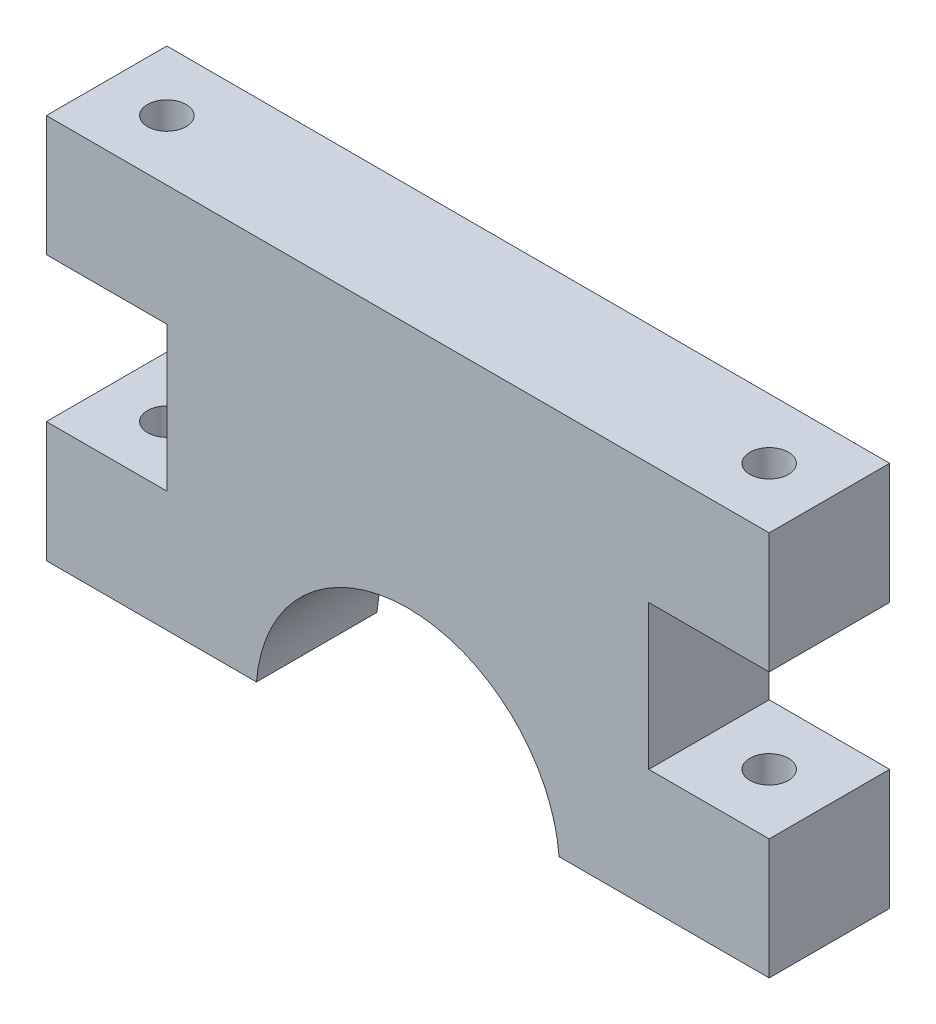
SolidWorks part; units mm, degrees
ref_plane "Спереди" through (0, 0, 0) normal (0, 0, 1) x (1, 0, 0)
ref_plane "Сверху" through (0, 0, 0) normal (0, 1, 0) x (1, 0, 0)
ref_plane "Справа" through (0, 0, 0) normal (1, 0, 0) x (0, 0, -1)
sketch "Эскиз1" plane through (0, 0, 0) normal (0, 0, 1) x (1, 0, 0)
  line L0 (12.5603, -16) -> (20, -16)
  line L1 (-20, -16) -> (-12.5603, -16)
  line L2 (-20, -16) -> (-20, 16)
  line L3 (-20, 16) -> (20, 16)
  line L4 (20, -16) -> (20, 16)
  line L5 (-20, -16) -> (20, 16) construction
  line L6 (-20, 16) -> (20, -16) construction
  line L7 (-20, -16) -> (-30, -16)
  line L8 (-20, -16) -> (-20, -6)
  line L9 (-20, -6) -> (-30, -6)
  line L10 (-30, -16) -> (-30, -6)
  line L11 (20, -16) -> (30, -16)
  line L12 (20, -16) -> (20, -6)
  line L13 (20, -6) -> (30, -6)
  line L14 (30, -16) -> (30, -6)
  line L15 (-20, 16) -> (-30, 16)
  line L16 (-20, 16) -> (-20, 6)
  line L17 (-20, 6) -> (-30, 6)
  line L18 (-30, 16) -> (-30, 6)
  line L19 (20, 16) -> (30, 16)
  line L20 (20, 16) -> (20, 6)
  line L21 (20, 6) -> (30, 6)
  line L22 (30, 16) -> (30, 6)
  arc A0 (12.5603, -16) -> (-12.5603, -16) centre (0, -17) ccw
  point P0 (0, 0)
  dimension "D3" = 25.2
  dimension "D1" = 40
  dimension "D2" = 32
  dimension "D4" = 1
  dimension "D5" = 10
  dimension "D6" = 10
extrude "Бобышка-Вытянуть1" add sketch "Эскиз1" along normal blind 10 contours L15 L18 L17 L2 | A0 L0 L4 L3 L2 L1 | L10 L7 L2 L9 | L22 L19 L4 L21 | L11 L14 L13 L4
sketch "Эскиз3" plane through (0, 16, 0) normal (0, 1, 0) x (1, 0, 0)
  line L0 (0, -10) -> (0, 0) construction
  line L1 (30, -10) -> (-30, -10) construction
  line L2 (-20, -10) -> (-30, -10) construction
  circle A0 centre (-25, -5) radius 1.6
  circle A1 centre (25, -5) radius 1.6
  point P7 (0, -5)
  point P8 (-25.6621, -5)
  point P9 (-25.546, -5)
  point P12 (-25, -10)
  dimension "D1" = 3.2
extrude "Вырез-Вытянуть1" cut sketch "Эскиз3" against normal blind 32
